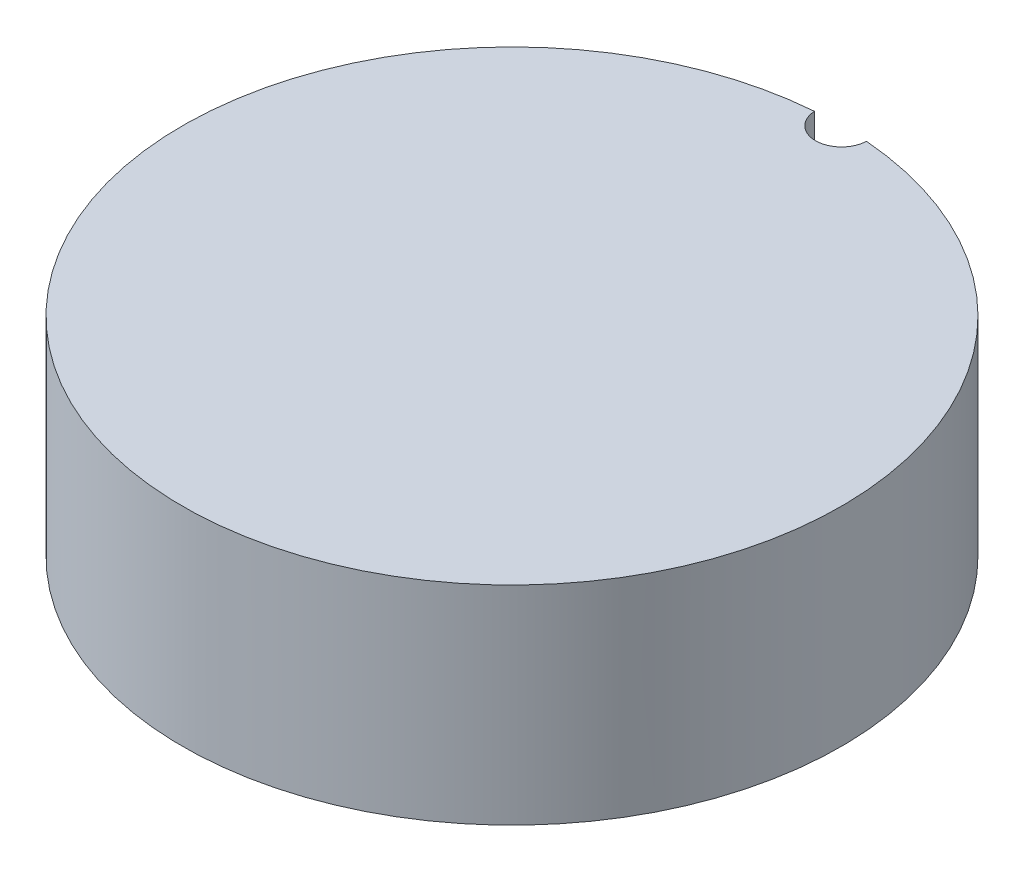
SolidWorks part; units mm, degrees
material "ABS"
ref_plane "Front Plane" through (0, 0, 0) normal (0, 0, 1) x (1, 0, 0)
ref_plane "Top Plane" through (0, 0, 0) normal (0, 1, 0) x (1, 0, 0)
ref_plane "Right Plane" through (0, 0, 0) normal (1, 0, 0) x (0, 0, -1)
sketch "Sketch1" plane through (0, 0, 0) normal (0, 0, 1) x (1, 0, 0)
  line L5 (0, 0) -> (0, -10)
  line L6 (0, -10) -> (-21.685, -10)
  line L7 (-31.685, -20) -> (-31.685, 0)
  line L8 (-31.685, 0) -> (0, 0)
  arc A2 (-21.685, -10) -> (-31.685, -20) centre (-21.685, -20) ccw
  dimension "D3" = 10
  dimension "D1" = 10
  dimension "D2" = 31.685
revolve "Main body" add sketch "Sketch1" angle 360 about L5
sketch "Sketch2" plane through (0, 0, 0) normal (0, 1, 0) x (1, 0, 0)
  arc A0 (-2.4981, 31.5864) -> (2.4981, 31.5864) centre (0, 31.685) ccw
  circle A1 centre (0, 0) radius 31.685 construction
  arc A2 (2.4981, 31.5864) -> (-2.4981, 31.5864) centre (0, 0) ccw
  point P3 (0, 0)
  point P7 (-1.1876, 31.1511)
  point P8 (0, 31.685)
  point P9 (-1.4079, 31.6537)
  point P10 (0, 0)
  point P11 (0, 0)
  dimension "D1" = 2.5
extrude "Second stage ignition wire passthrough" cut sketch "Sketch2" against normal through all both and the other way through all
